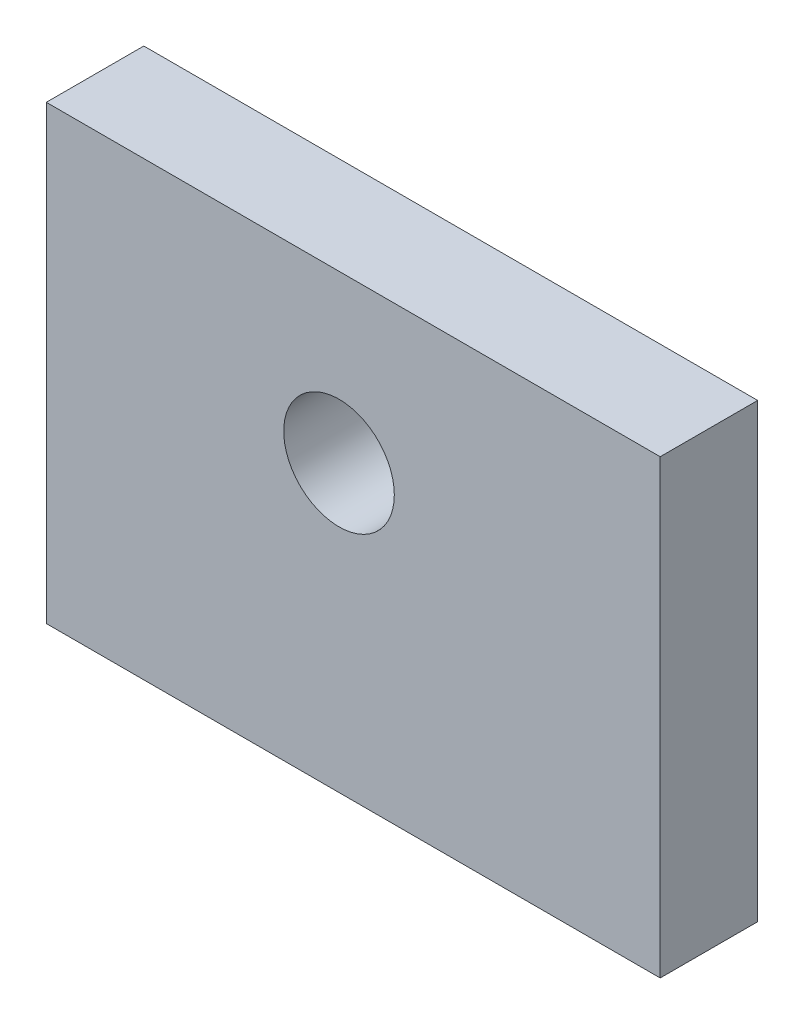
SolidWorks part; units mm, degrees
ref_plane "Front Plane" through (0, 0, 0) normal (0, 0, 1) x (1, 0, 0)
ref_plane "Top Plane" through (0, 0, 0) normal (0, 1, 0) x (1, 0, 0)
ref_plane "Right Plane" through (0, 0, 0) normal (1, 0, 0) x (0, 0, -1)
other "Configuration Table"
sketch "Sketch1" plane through (0, 0, 0) normal (0, 0, 1) x (1, 0, 0)
  line L1 (-74.3522, 32.1081) -> (83.075, 32.1081)
  line L2 (-74.3522, 32.1081) -> (-74.3522, -83.6666)
  line L3 (-74.3522, -83.6666) -> (83.075, -83.6666)
  line L4 (83.075, 32.1081) -> (83.075, -83.6666)
extrude "Boss-Extrude1" add sketch "Sketch1" against normal blind 25
sketch "Sketch2" plane through (0, 0, 0) normal (0, 0, 1) x (1, 0, 0)
  circle A0 centre (0.7097, -10.4763) radius 14.1803
extrude "Cut-Extrude1" cut sketch "Sketch2" against normal through all
